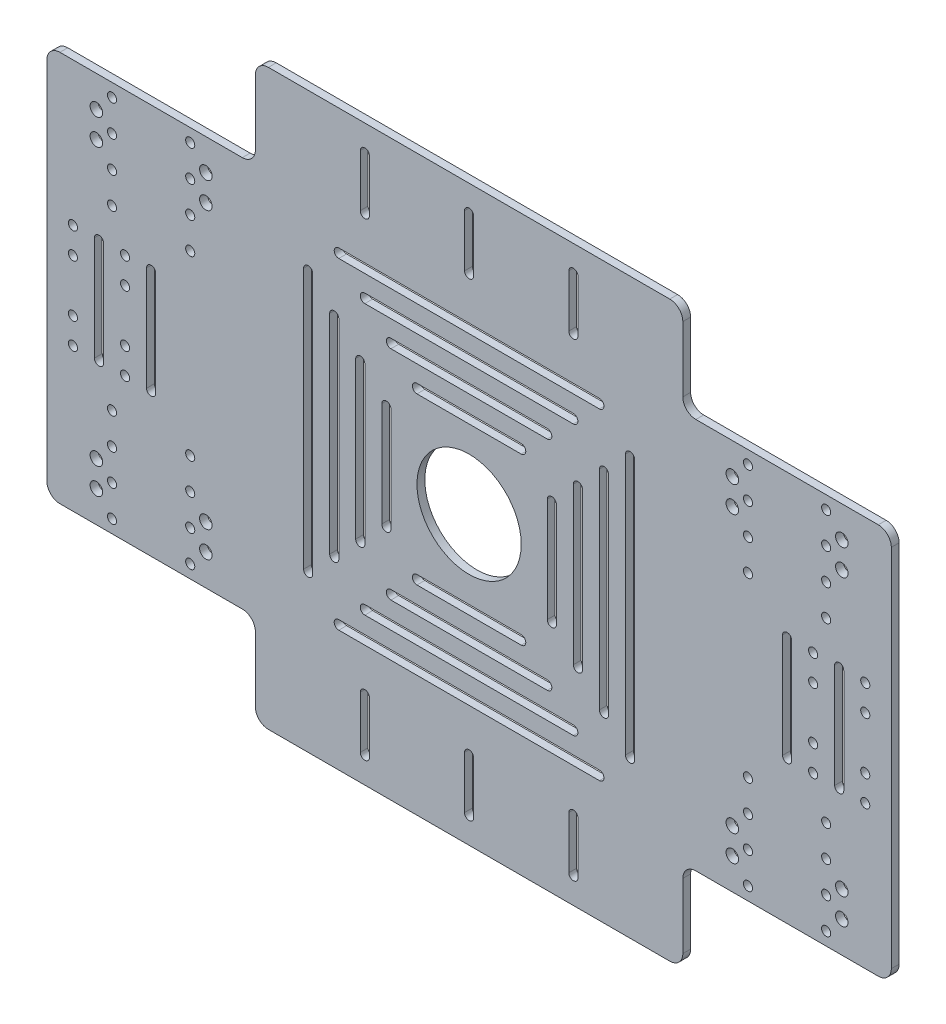
SolidWorks part; units mm, degrees
ref_plane "Front Plane" through (0, 0, 0) normal (0, 0, 1) x (1, 0, 0)
ref_plane "Top Plane" through (0, 0, 0) normal (0, 1, 0) x (1, 0, 0)
ref_plane "Right Plane" through (0, 0, 0) normal (1, 0, 0) x (0, 0, -1)
sketch "Model" plane through (0, 0, 0) normal (0, 0, 1) x (1, 0, 0)
  line L0 (-287, 200) -> (-287, -200)
  line L1 (-287, -200) -> (287, -200)
  line L2 (287, -200) -> (287, 200)
  line L3 (287, 200) -> (-287, 200)
  line L4 (287, -200) -> (287, -144)
  line L5 (287, -144) -> (107, -144)
  line L6 (107, -144) -> (107, -200)
  line L7 (287, -200) -> (107, -200)
  line L8 (187, -144) -> (187, -200)
  line L9 (237, -144) -> (237, -200)
  line L10 (187, -193) -> (107, -193)
  line L11 (187, -186) -> (107, -186)
  line L12 (187, -179) -> (107, -179)
  line L13 (147, -172) -> (147, -200)
  line L14 (213, -172) -> (213, -191)
  line L15 (225, -172) -> (225, -191)
  line L16 (237, -172) -> (107, -172)
  line L17 (287, -179) -> (237, -179)
  line L18 (287, -161) -> (237, -161)
  line L19 (287, -191) -> (187, -191)
  line L20 (-119.2105, 180.4807) -> (-119.2105, 155.4807)
  line L21 (-119.2105, -4.5193) -> (-119.2105, -29.5193)
  line L22 (44.7895, -29.5193) -> (44.7895, -4.5193)
  line L23 (44.7895, 155.4807) -> (44.7895, 180.4807)
  line L24 (39.7895, 185.4807) -> (-99.2105, 185.4807)
  line L25 (-99.2105, 185.4807) -> (-114.2105, 185.4807)
  line L26 (-114.2105, -34.5193) -> (-96.2105, -34.5193)
  line L27 (-96.2105, -34.5193) -> (39.7895, -34.5193)
  line L28 (124.7895, 5.4807) -> (124.7895, 76.9807)
  line L29 (124.7895, 76.9807) -> (124.7895, 145.4807)
  line L30 (-199.2105, 145.4807) -> (-199.2105, 76.9807)
  line L31 (-199.2105, 76.9807) -> (-199.2105, 5.4807)
  line L32 (-124.2105, 150.4807) -> (-194.2105, 150.4807)
  line L33 (-124.2105, 0.4807) -> (-194.2105, 0.4807)
  line L34 (49.7895, 0.4807) -> (119.7895, 0.4807)
  line L35 (49.7895, 150.4807) -> (119.7895, 150.4807)
  line L36 (-17.2105, 105.4807) -> (-37.2105, 105.4807)
  line L37 (-7.2105, 115.4807) -> (-37.2105, 115.4807)
  line L38 (2.7895, 125.4807) -> (-37.2105, 125.4807)
  line L39 (12.7895, 135.4807) -> (-37.2105, 135.4807)
  line L40 (-17.2105, 108.9807) -> (-37.2105, 108.9807)
  line L41 (-7.2105, 118.9807) -> (-37.2105, 118.9807)
  line L42 (2.7895, 128.9807) -> (-37.2105, 128.9807)
  line L43 (12.7895, 138.9807) -> (-37.2105, 138.9807)
  line L44 (-57.2105, 105.4807) -> (-37.2105, 105.4807)
  line L45 (-67.2105, 115.4807) -> (-37.2105, 115.4807)
  line L46 (-77.2105, 125.4807) -> (-37.2105, 125.4807)
  line L47 (-87.2105, 135.4807) -> (-37.2105, 135.4807)
  line L48 (-57.2105, 108.9807) -> (-37.2105, 108.9807)
  line L49 (-67.2105, 118.9807) -> (-37.2105, 118.9807)
  line L50 (-77.2105, 128.9807) -> (-37.2105, 128.9807)
  line L51 (-87.2105, 138.9807) -> (-37.2105, 138.9807)
  line L52 (-67.2105, 95.4807) -> (-67.2105, 75.4807)
  line L53 (-77.2105, 105.4807) -> (-77.2105, 75.4807)
  line L54 (-87.2105, 115.4807) -> (-87.2105, 75.4807)
  line L55 (-97.2105, 125.4807) -> (-97.2105, 75.4807)
  line L56 (-70.7105, 95.4807) -> (-70.7105, 75.4807)
  line L57 (-80.7105, 105.4807) -> (-80.7105, 75.4807)
  line L58 (-90.7105, 115.4807) -> (-90.7105, 75.4807)
  line L59 (-100.7105, 125.4807) -> (-100.7105, 75.4807)
  line L60 (-67.2105, 55.4807) -> (-67.2105, 75.4807)
  line L61 (-77.2105, 45.4807) -> (-77.2105, 75.4807)
  line L62 (-87.2105, 35.4807) -> (-87.2105, 75.4807)
  line L63 (-97.2105, 25.4807) -> (-97.2105, 75.4807)
  line L64 (-70.7105, 55.4807) -> (-70.7105, 75.4807)
  line L65 (-80.7105, 45.4807) -> (-80.7105, 75.4807)
  line L66 (-90.7105, 35.4807) -> (-90.7105, 75.4807)
  line L67 (-100.7105, 25.4807) -> (-100.7105, 75.4807)
  line L68 (-57.2105, 45.4807) -> (-37.2105, 45.4807)
  line L69 (-67.2105, 35.4807) -> (-37.2105, 35.4807)
  line L70 (-77.2105, 25.4807) -> (-37.2105, 25.4807)
  line L71 (-87.2105, 15.4807) -> (-37.2105, 15.4807)
  line L72 (-57.2105, 41.9807) -> (-37.2105, 41.9807)
  line L73 (-67.2105, 31.9807) -> (-37.2105, 31.9807)
  line L74 (-77.2105, 21.9807) -> (-37.2105, 21.9807)
  line L75 (-87.2105, 11.9807) -> (-37.2105, 11.9807)
  line L76 (-17.2105, 45.4807) -> (-37.2105, 45.4807)
  line L77 (-7.2105, 35.4807) -> (-37.2105, 35.4807)
  line L78 (2.7895, 25.4807) -> (-37.2105, 25.4807)
  line L79 (12.7895, 15.4807) -> (-37.2105, 15.4807)
  line L80 (-17.2105, 41.9807) -> (-37.2105, 41.9807)
  line L81 (-7.2105, 31.9807) -> (-37.2105, 31.9807)
  line L82 (2.7895, 21.9807) -> (-37.2105, 21.9807)
  line L83 (12.7895, 11.9807) -> (-37.2105, 11.9807)
  line L84 (-7.2105, 55.4807) -> (-7.2105, 75.4807)
  line L85 (2.7895, 45.4807) -> (2.7895, 75.4807)
  line L86 (12.7895, 35.4807) -> (12.7895, 75.4807)
  line L87 (22.7895, 25.4807) -> (22.7895, 75.4807)
  line L88 (-3.7105, 55.4807) -> (-3.7105, 75.4807)
  line L89 (6.2895, 45.4807) -> (6.2895, 75.4807)
  line L90 (16.2895, 35.4807) -> (16.2895, 75.4807)
  line L91 (26.2895, 25.4807) -> (26.2895, 75.4807)
  line L92 (-7.2105, 95.4807) -> (-7.2105, 75.4807)
  line L93 (2.7895, 105.4807) -> (2.7895, 75.4807)
  line L94 (12.7895, 115.4807) -> (12.7895, 75.4807)
  line L95 (22.7895, 125.4807) -> (22.7895, 75.4807)
  line L96 (-3.7105, 95.4807) -> (-3.7105, 75.4807)
  line L97 (6.2895, 105.4807) -> (6.2895, 75.4807)
  line L98 (16.2895, 115.4807) -> (16.2895, 75.4807)
  line L99 (26.2895, 125.4807) -> (26.2895, 75.4807)
  line L100 (-180.9605, 95.4807) -> (-180.9605, 55.4807)
  line L101 (-177.4605, 95.4807) -> (-177.4605, 55.4807)
  line L102 (-160.9605, 95.4807) -> (-160.9605, 55.4807)
  line L103 (-157.4605, 95.4807) -> (-157.4605, 55.4807)
  line L104 (106.5395, 95.4807) -> (106.5395, 55.4807)
  line L105 (103.0395, 95.4807) -> (103.0395, 55.4807)
  line L106 (86.5395, 95.4807) -> (86.5395, 55.4807)
  line L107 (83.0395, 95.4807) -> (83.0395, 55.4807)
  line L108 (-78.9605, 175.4807) -> (-78.9605, 155.4807)
  line L109 (-75.4605, 175.4807) -> (-75.4605, 155.4807)
  line L110 (-38.9605, 175.4807) -> (-38.9605, 155.4807)
  line L111 (-35.4605, 175.4807) -> (-35.4605, 155.4807)
  line L112 (4.5395, 175.4807) -> (4.5395, 155.4807)
  line L113 (1.0395, 175.4807) -> (1.0395, 155.4807)
  line L114 (-78.9605, -24.5193) -> (-78.9605, -4.5193)
  line L115 (-75.4605, -24.5193) -> (-75.4605, -4.5193)
  line L116 (-38.9605, -24.5193) -> (-38.9605, -4.5193)
  line L117 (-35.4605, -24.5193) -> (-35.4605, -4.5193)
  line L118 (4.5395, -24.5193) -> (4.5395, -4.5193)
  line L119 (1.0395, -24.5193) -> (1.0395, -4.5193)
  line L120 (210.9858, 185.4807) -> (213.9858, 185.4807)
  line L121 (213.9858, 185.4807) -> (213.9858, -33.4042)
  line L122 (210.9858, 185.4807) -> (210.9858, -33.4042)
  line L123 (210.9858, -33.4042) -> (213.9858, -33.4042)
  line L124 (210.9858, 150.4807) -> (213.9858, 150.4807)
  line L125 (210.9858, 0.4807) -> (213.9858, 0.4807)
  circle A0 centre (-180.2105, 138.4807) radius 2.4
  circle A1 centre (-138.2105, 138.4807) radius 2.4
  circle A2 centre (-180.2105, 128.4807) radius 2.4
  circle A3 centre (-138.2105, 128.4807) radius 2.4
  circle A4 centre (-180.2105, 12.4807) radius 2.4
  circle A5 centre (-138.2105, 12.4807) radius 2.4
  circle A6 centre (-180.2105, 22.4807) radius 2.4
  circle A7 centre (-138.2105, 22.4807) radius 2.4
  circle A8 centre (105.7895, 12.4807) radius 2.4
  circle A9 centre (63.7895, 12.4807) radius 2.4
  circle A10 centre (105.7895, 22.4807) radius 2.4
  circle A11 centre (63.7895, 22.4807) radius 2.4
  circle A12 centre (105.7895, 138.4807) radius 2.4
  circle A13 centre (63.7895, 138.4807) radius 2.4
  circle A14 centre (105.7895, 128.4807) radius 2.4
  circle A15 centre (63.7895, 128.4807) radius 2.4
  circle A16 centre (-144.2105, 17.4807) radius 1.75
  circle A17 centre (-144.2105, 5.4807) radius 1.75
  circle A18 centre (-144.2105, 29.4807) radius 1.75
  circle A19 centre (-144.2105, 41.4807) radius 1.75
  circle A20 centre (-174.2105, 17.4807) radius 1.75
  circle A21 centre (-174.2105, 5.4807) radius 1.75
  circle A22 centre (-174.2105, 29.4807) radius 1.75
  circle A23 centre (-174.2105, 41.4807) radius 1.75
  circle A24 centre (-144.2105, 133.4807) radius 1.75
  circle A25 centre (-144.2105, 145.4807) radius 1.75
  circle A26 centre (-144.2105, 121.4807) radius 1.75
  circle A27 centre (-144.2105, 109.4807) radius 1.75
  circle A28 centre (-174.2105, 133.4807) radius 1.75
  circle A29 centre (-174.2105, 145.4807) radius 1.75
  circle A30 centre (-174.2105, 121.4807) radius 1.75
  circle A31 centre (-174.2105, 109.4807) radius 1.75
  circle A32 centre (69.7895, 133.4807) radius 1.75
  circle A33 centre (69.7895, 145.4807) radius 1.75
  circle A34 centre (69.7895, 121.4807) radius 1.75
  circle A35 centre (69.7895, 109.4807) radius 1.75
  circle A36 centre (99.7895, 133.4807) radius 1.75
  circle A37 centre (99.7895, 145.4807) radius 1.75
  circle A38 centre (99.7895, 121.4807) radius 1.75
  circle A39 centre (99.7895, 109.4807) radius 1.75
  circle A40 centre (69.7895, 17.4807) radius 1.75
  circle A41 centre (69.7895, 5.4807) radius 1.75
  circle A42 centre (69.7895, 29.4807) radius 1.75
  circle A43 centre (69.7895, 41.4807) radius 1.75
  circle A44 centre (99.7895, 17.4807) radius 1.75
  circle A45 centre (99.7895, 5.4807) radius 1.75
  circle A46 centre (99.7895, 29.4807) radius 1.75
  circle A47 centre (99.7895, 41.4807) radius 1.75
  arc A48 (-194.2105, 150.4807) -> (-199.2105, 145.4807) centre (-194.2105, 145.4807) ccw
  arc A49 (-124.2105, 150.4807) -> (-119.2105, 155.4807) centre (-124.2105, 155.4807) ccw
  arc A50 (-199.2105, 5.4807) -> (-194.2105, 0.4807) centre (-194.2105, 5.4807) ccw
  arc A51 (-119.2105, -4.5193) -> (-124.2105, 0.4807) centre (-124.2105, -4.5193) ccw
  arc A52 (-119.2105, -29.5193) -> (-114.2105, -34.5193) centre (-114.2105, -29.5193) ccw
  arc A53 (39.7895, -34.5193) -> (44.7895, -29.5193) centre (39.7895, -29.5193) ccw
  arc A54 (49.7895, 0.4807) -> (44.7895, -4.5193) centre (49.7895, -4.5193) ccw
  arc A55 (119.7895, 0.4807) -> (124.7895, 5.4807) centre (119.7895, 5.4807) ccw
  arc A56 (124.7895, 145.4807) -> (119.7895, 150.4807) centre (119.7895, 145.4807) ccw
  arc A57 (44.7895, 155.4807) -> (49.7895, 150.4807) centre (49.7895, 155.4807) ccw
  arc A58 (44.7895, 180.4807) -> (39.7895, 185.4807) centre (39.7895, 180.4807) ccw
  arc A59 (-114.2105, 185.4807) -> (-119.2105, 180.4807) centre (-114.2105, 180.4807) ccw
  circle A60 centre (-37.2105, 75.4807) radius 20
  arc A61 (12.7895, 135.4807) -> (12.7895, 138.9807) centre (12.7895, 137.2307) ccw
  arc A62 (2.7895, 125.4807) -> (2.7895, 128.9807) centre (2.7895, 127.2307) ccw
  arc A63 (-7.2105, 115.4807) -> (-7.2105, 118.9807) centre (-7.2105, 117.2307) ccw
  arc A64 (-17.2105, 105.4807) -> (-17.2105, 108.9807) centre (-17.2105, 107.2307) ccw
  arc A65 (-87.2105, 138.9807) -> (-87.2105, 135.4807) centre (-87.2105, 137.2307) ccw
  arc A66 (-77.2105, 128.9807) -> (-77.2105, 125.4807) centre (-77.2105, 127.2307) ccw
  arc A67 (-67.2105, 118.9807) -> (-67.2105, 115.4807) centre (-67.2105, 117.2307) ccw
  arc A68 (-57.2105, 108.9807) -> (-57.2105, 105.4807) centre (-57.2105, 107.2307) ccw
  arc A69 (-97.2105, 125.4807) -> (-100.7105, 125.4807) centre (-98.9605, 125.4807) ccw
  arc A70 (-87.2105, 115.4807) -> (-90.7105, 115.4807) centre (-88.9605, 115.4807) ccw
  arc A71 (-77.2105, 105.4807) -> (-80.7105, 105.4807) centre (-78.9605, 105.4807) ccw
  arc A72 (-67.2105, 95.4807) -> (-70.7105, 95.4807) centre (-68.9605, 95.4807) ccw
  arc A73 (-100.7105, 25.4807) -> (-97.2105, 25.4807) centre (-98.9605, 25.4807) ccw
  arc A74 (-90.7105, 35.4807) -> (-87.2105, 35.4807) centre (-88.9605, 35.4807) ccw
  arc A75 (-80.7105, 45.4807) -> (-77.2105, 45.4807) centre (-78.9605, 45.4807) ccw
  arc A76 (-70.7105, 55.4807) -> (-67.2105, 55.4807) centre (-68.9605, 55.4807) ccw
  arc A77 (-87.2105, 15.4807) -> (-87.2105, 11.9807) centre (-87.2105, 13.7307) ccw
  arc A78 (-77.2105, 25.4807) -> (-77.2105, 21.9807) centre (-77.2105, 23.7307) ccw
  arc A79 (-67.2105, 35.4807) -> (-67.2105, 31.9807) centre (-67.2105, 33.7307) ccw
  arc A80 (-57.2105, 45.4807) -> (-57.2105, 41.9807) centre (-57.2105, 43.7307) ccw
  arc A81 (12.7895, 11.9807) -> (12.7895, 15.4807) centre (12.7895, 13.7307) ccw
  arc A82 (2.7895, 21.9807) -> (2.7895, 25.4807) centre (2.7895, 23.7307) ccw
  arc A83 (-7.2105, 31.9807) -> (-7.2105, 35.4807) centre (-7.2105, 33.7307) ccw
  arc A84 (-17.2105, 41.9807) -> (-17.2105, 45.4807) centre (-17.2105, 43.7307) ccw
  arc A85 (22.7895, 25.4807) -> (26.2895, 25.4807) centre (24.5395, 25.4807) ccw
  arc A86 (12.7895, 35.4807) -> (16.2895, 35.4807) centre (14.5395, 35.4807) ccw
  arc A87 (2.7895, 45.4807) -> (6.2895, 45.4807) centre (4.5395, 45.4807) ccw
  arc A88 (-7.2105, 55.4807) -> (-3.7105, 55.4807) centre (-5.4605, 55.4807) ccw
  arc A89 (26.2895, 125.4807) -> (22.7895, 125.4807) centre (24.5395, 125.4807) ccw
  arc A90 (16.2895, 115.4807) -> (12.7895, 115.4807) centre (14.5395, 115.4807) ccw
  arc A91 (6.2895, 105.4807) -> (2.7895, 105.4807) centre (4.5395, 105.4807) ccw
  arc A92 (-3.7105, 95.4807) -> (-7.2105, 95.4807) centre (-5.4605, 95.4807) ccw
  circle A93 centre (-189.2105, 85.4807) radius 1.75
  circle A94 centre (-189.2105, 95.4807) radius 1.75
  circle A95 centre (-169.2105, 95.4807) radius 1.75
  circle A96 centre (-169.2105, 85.4807) radius 1.75
  circle A97 centre (-189.2105, 65.4807) radius 1.75
  circle A98 centre (-189.2105, 55.4807) radius 1.75
  circle A99 centre (-169.2105, 55.4807) radius 1.75
  circle A100 centre (-169.2105, 65.4807) radius 1.75
  arc A101 (-177.4605, 95.4807) -> (-180.9605, 95.4807) centre (-179.2105, 95.4807) ccw
  arc A102 (-180.9605, 55.4807) -> (-177.4605, 55.4807) centre (-179.2105, 55.4807) ccw
  arc A103 (-160.9605, 55.4807) -> (-157.4605, 55.4807) centre (-159.2105, 55.4807) ccw
  arc A104 (-157.4605, 95.4807) -> (-160.9605, 95.4807) centre (-159.2105, 95.4807) ccw
  circle A105 centre (114.7895, 85.4807) radius 1.75
  circle A106 centre (114.7895, 95.4807) radius 1.75
  circle A107 centre (94.7895, 95.4807) radius 1.75
  circle A108 centre (94.7895, 85.4807) radius 1.75
  circle A109 centre (114.7895, 65.4807) radius 1.75
  circle A110 centre (114.7895, 55.4807) radius 1.75
  circle A111 centre (94.7895, 55.4807) radius 1.75
  circle A112 centre (94.7895, 65.4807) radius 1.75
  arc A113 (106.5395, 95.4807) -> (103.0395, 95.4807) centre (104.7895, 95.4807) ccw
  arc A114 (103.0395, 55.4807) -> (106.5395, 55.4807) centre (104.7895, 55.4807) ccw
  arc A115 (83.0395, 55.4807) -> (86.5395, 55.4807) centre (84.7895, 55.4807) ccw
  arc A116 (86.5395, 95.4807) -> (83.0395, 95.4807) centre (84.7895, 95.4807) ccw
  arc A117 (-75.4605, 175.4807) -> (-78.9605, 175.4807) centre (-77.2105, 175.4807) ccw
  arc A118 (-78.9605, 155.4807) -> (-75.4605, 155.4807) centre (-77.2105, 155.4807) ccw
  arc A119 (-38.9605, 155.4807) -> (-35.4605, 155.4807) centre (-37.2105, 155.4807) ccw
  arc A120 (-35.4605, 175.4807) -> (-38.9605, 175.4807) centre (-37.2105, 175.4807) ccw
  arc A121 (4.5395, 175.4807) -> (1.0395, 175.4807) centre (2.7895, 175.4807) ccw
  arc A122 (1.0395, 155.4807) -> (4.5395, 155.4807) centre (2.7895, 155.4807) ccw
  arc A123 (-78.9605, -24.5193) -> (-75.4605, -24.5193) centre (-77.2105, -24.5193) ccw
  arc A124 (-75.4605, -4.5193) -> (-78.9605, -4.5193) centre (-77.2105, -4.5193) ccw
  arc A125 (-35.4605, -4.5193) -> (-38.9605, -4.5193) centre (-37.2105, -4.5193) ccw
  arc A126 (-38.9605, -24.5193) -> (-35.4605, -24.5193) centre (-37.2105, -24.5193) ccw
  arc A127 (1.0395, -24.5193) -> (4.5395, -24.5193) centre (2.7895, -24.5193) ccw
  arc A128 (4.5395, -4.5193) -> (1.0395, -4.5193) centre (2.7895, -4.5193) ccw
sketch "Sketch2" plane through (0, 0, 0) normal (0, 0, 1) x (1, 0, 0)
  line L0 (-124.2105, 150.4807) -> (-194.2105, 150.4807) construction
  line L1 (-119.2105, 180.4807) -> (-119.2105, 155.4807) construction
  line L2 (-99.2105, 185.4807) -> (-114.2105, 185.4807) construction
  line L3 (39.7895, 185.4807) -> (-99.2105, 185.4807) construction
  line L4 (44.7895, 155.4807) -> (44.7895, 180.4807) construction
  line L5 (49.7895, 150.4807) -> (119.7895, 150.4807) construction
  line L6 (124.7895, 76.9807) -> (124.7895, 145.4807) construction
  line L7 (124.7895, 5.4807) -> (124.7895, 76.9807) construction
  line L8 (49.7895, 0.4807) -> (119.7895, 0.4807) construction
  line L9 (44.7895, -29.5193) -> (44.7895, -4.5193) construction
  line L10 (-96.2105, -34.5193) -> (39.7895, -34.5193) construction
  line L11 (-114.2105, -34.5193) -> (-96.2105, -34.5193) construction
  line L12 (-119.2105, -4.5193) -> (-119.2105, -29.5193) construction
  line L13 (-124.2105, 0.4807) -> (-194.2105, 0.4807) construction
  line L14 (-199.2105, 76.9807) -> (-199.2105, 5.4807) construction
  line L15 (-199.2105, 145.4807) -> (-199.2105, 76.9807) construction
  line L16 (-124.2105, 150.4807) -> (-194.2105, 150.4807)
  line L17 (-119.2105, 180.4807) -> (-119.2105, 155.4807)
  line L18 (-99.2105, 185.4807) -> (-114.2105, 185.4807)
  line L19 (39.7895, 185.4807) -> (-99.2105, 185.4807)
  line L20 (44.7895, 155.4807) -> (44.7895, 180.4807)
  line L21 (49.7895, 150.4807) -> (119.7895, 150.4807)
  line L22 (124.7895, 76.9807) -> (124.7895, 145.4807)
  line L23 (124.7895, 5.4807) -> (124.7895, 76.9807)
  line L24 (49.7895, 0.4807) -> (119.7895, 0.4807)
  line L25 (44.7895, -29.5193) -> (44.7895, -4.5193)
  line L26 (-96.2105, -34.5193) -> (39.7895, -34.5193)
  line L27 (-114.2105, -34.5193) -> (-96.2105, -34.5193)
  line L28 (-119.2105, -4.5193) -> (-119.2105, -29.5193)
  line L29 (-124.2105, 0.4807) -> (-194.2105, 0.4807)
  line L30 (-199.2105, 76.9807) -> (-199.2105, 5.4807)
  line L31 (-199.2105, 145.4807) -> (-199.2105, 76.9807)
  line L32 (-78.9605, 175.4807) -> (-78.9605, 155.4807) construction
  line L33 (-75.4605, 175.4807) -> (-75.4605, 155.4807) construction
  line L34 (-78.9605, 175.4807) -> (-78.9605, 155.4807)
  line L35 (-75.4605, 175.4807) -> (-75.4605, 155.4807)
  line L36 (-38.9605, 175.4807) -> (-38.9605, 155.4807) construction
  line L37 (-35.4605, 175.4807) -> (-35.4605, 155.4807) construction
  line L38 (-38.9605, 175.4807) -> (-38.9605, 155.4807)
  line L39 (-35.4605, 175.4807) -> (-35.4605, 155.4807)
  line L40 (4.5395, 175.4807) -> (4.5395, 155.4807) construction
  line L41 (1.0395, 175.4807) -> (1.0395, 155.4807) construction
  line L42 (4.5395, 175.4807) -> (4.5395, 155.4807)
  line L43 (1.0395, 175.4807) -> (1.0395, 155.4807)
  line L44 (-87.2105, 138.9807) -> (-37.2105, 138.9807) construction
  line L45 (12.7895, 138.9807) -> (-37.2105, 138.9807) construction
  line L46 (12.7895, 135.4807) -> (-37.2105, 135.4807) construction
  line L47 (-87.2105, 135.4807) -> (-37.2105, 135.4807) construction
  line L48 (-87.2105, 138.9807) -> (-37.2105, 138.9807)
  line L49 (12.7895, 138.9807) -> (-37.2105, 138.9807)
  line L50 (12.7895, 135.4807) -> (-37.2105, 135.4807)
  line L51 (-87.2105, 135.4807) -> (-37.2105, 135.4807)
  line L52 (-77.2105, 128.9807) -> (-37.2105, 128.9807) construction
  line L53 (2.7895, 128.9807) -> (-37.2105, 128.9807) construction
  line L54 (2.7895, 125.4807) -> (-37.2105, 125.4807) construction
  line L55 (-77.2105, 125.4807) -> (-37.2105, 125.4807) construction
  line L56 (-77.2105, 128.9807) -> (-37.2105, 128.9807)
  line L57 (2.7895, 128.9807) -> (-37.2105, 128.9807)
  line L58 (2.7895, 125.4807) -> (-37.2105, 125.4807)
  line L59 (-77.2105, 125.4807) -> (-37.2105, 125.4807)
  line L60 (-67.2105, 118.9807) -> (-37.2105, 118.9807) construction
  line L61 (-7.2105, 118.9807) -> (-37.2105, 118.9807) construction
  line L62 (-7.2105, 115.4807) -> (-37.2105, 115.4807) construction
  line L63 (-67.2105, 115.4807) -> (-37.2105, 115.4807) construction
  line L64 (-67.2105, 118.9807) -> (-37.2105, 118.9807)
  line L65 (-7.2105, 118.9807) -> (-37.2105, 118.9807)
  line L66 (-7.2105, 115.4807) -> (-37.2105, 115.4807)
  line L67 (-67.2105, 115.4807) -> (-37.2105, 115.4807)
  line L68 (-57.2105, 108.9807) -> (-37.2105, 108.9807) construction
  line L69 (-17.2105, 108.9807) -> (-37.2105, 108.9807) construction
  line L70 (-17.2105, 105.4807) -> (-37.2105, 105.4807) construction
  line L71 (-57.2105, 105.4807) -> (-37.2105, 105.4807) construction
  line L72 (-57.2105, 108.9807) -> (-37.2105, 108.9807)
  line L73 (-17.2105, 108.9807) -> (-37.2105, 108.9807)
  line L74 (-17.2105, 105.4807) -> (-37.2105, 105.4807)
  line L75 (-57.2105, 105.4807) -> (-37.2105, 105.4807)
  line L76 (-100.7105, 25.4807) -> (-100.7105, 75.4807) construction
  line L77 (-100.7105, 125.4807) -> (-100.7105, 75.4807) construction
  line L78 (-97.2105, 125.4807) -> (-97.2105, 75.4807) construction
  line L79 (-97.2105, 25.4807) -> (-97.2105, 75.4807) construction
  line L80 (-100.7105, 25.4807) -> (-100.7105, 75.4807)
  line L81 (-100.7105, 125.4807) -> (-100.7105, 75.4807)
  line L82 (-97.2105, 125.4807) -> (-97.2105, 75.4807)
  line L83 (-97.2105, 25.4807) -> (-97.2105, 75.4807)
  line L84 (-90.7105, 115.4807) -> (-90.7105, 75.4807) construction
  line L85 (-90.7105, 35.4807) -> (-90.7105, 75.4807) construction
  line L86 (-87.2105, 35.4807) -> (-87.2105, 75.4807) construction
  line L87 (-87.2105, 115.4807) -> (-87.2105, 75.4807) construction
  line L88 (-90.7105, 115.4807) -> (-90.7105, 75.4807)
  line L89 (-90.7105, 35.4807) -> (-90.7105, 75.4807)
  line L90 (-87.2105, 35.4807) -> (-87.2105, 75.4807)
  line L91 (-87.2105, 115.4807) -> (-87.2105, 75.4807)
  line L92 (-80.7105, 105.4807) -> (-80.7105, 75.4807) construction
  line L93 (-80.7105, 45.4807) -> (-80.7105, 75.4807) construction
  line L94 (-77.2105, 45.4807) -> (-77.2105, 75.4807) construction
  line L95 (-77.2105, 105.4807) -> (-77.2105, 75.4807) construction
  line L96 (-80.7105, 105.4807) -> (-80.7105, 75.4807)
  line L97 (-80.7105, 45.4807) -> (-80.7105, 75.4807)
  line L98 (-77.2105, 45.4807) -> (-77.2105, 75.4807)
  line L99 (-77.2105, 105.4807) -> (-77.2105, 75.4807)
  line L100 (-70.7105, 95.4807) -> (-70.7105, 75.4807) construction
  line L101 (-70.7105, 55.4807) -> (-70.7105, 75.4807) construction
  line L102 (-67.2105, 55.4807) -> (-67.2105, 75.4807) construction
  line L103 (-67.2105, 95.4807) -> (-67.2105, 75.4807) construction
  line L104 (-70.7105, 95.4807) -> (-70.7105, 75.4807)
  line L105 (-70.7105, 55.4807) -> (-70.7105, 75.4807)
  line L106 (-67.2105, 55.4807) -> (-67.2105, 75.4807)
  line L107 (-67.2105, 95.4807) -> (-67.2105, 75.4807)
  line L108 (-160.9605, 95.4807) -> (-160.9605, 55.4807) construction
  line L109 (-157.4605, 95.4807) -> (-157.4605, 55.4807) construction
  line L110 (-160.9605, 95.4807) -> (-160.9605, 55.4807)
  line L111 (-157.4605, 95.4807) -> (-157.4605, 55.4807)
  line L112 (-180.9605, 95.4807) -> (-180.9605, 55.4807) construction
  line L113 (-177.4605, 95.4807) -> (-177.4605, 55.4807) construction
  line L114 (-180.9605, 95.4807) -> (-180.9605, 55.4807)
  line L115 (-177.4605, 95.4807) -> (-177.4605, 55.4807)
  line L116 (-57.2105, 45.4807) -> (-37.2105, 45.4807) construction
  line L117 (-17.2105, 45.4807) -> (-37.2105, 45.4807) construction
  line L118 (-17.2105, 41.9807) -> (-37.2105, 41.9807) construction
  line L119 (-57.2105, 41.9807) -> (-37.2105, 41.9807) construction
  line L120 (-67.2105, 35.4807) -> (-37.2105, 35.4807) construction
  line L121 (-7.2105, 35.4807) -> (-37.2105, 35.4807) construction
  line L122 (-7.2105, 31.9807) -> (-37.2105, 31.9807) construction
  line L123 (-67.2105, 31.9807) -> (-37.2105, 31.9807) construction
  line L124 (-77.2105, 25.4807) -> (-37.2105, 25.4807) construction
  line L125 (2.7895, 25.4807) -> (-37.2105, 25.4807) construction
  line L126 (2.7895, 21.9807) -> (-37.2105, 21.9807) construction
  line L127 (-77.2105, 21.9807) -> (-37.2105, 21.9807) construction
  line L128 (-87.2105, 15.4807) -> (-37.2105, 15.4807) construction
  line L129 (12.7895, 15.4807) -> (-37.2105, 15.4807) construction
  line L130 (12.7895, 11.9807) -> (-37.2105, 11.9807) construction
  line L131 (-87.2105, 11.9807) -> (-37.2105, 11.9807) construction
  line L132 (-57.2105, 45.4807) -> (-37.2105, 45.4807)
  line L133 (-17.2105, 45.4807) -> (-37.2105, 45.4807)
  line L134 (-17.2105, 41.9807) -> (-37.2105, 41.9807)
  line L135 (-57.2105, 41.9807) -> (-37.2105, 41.9807)
  line L136 (-67.2105, 35.4807) -> (-37.2105, 35.4807)
  line L137 (-7.2105, 35.4807) -> (-37.2105, 35.4807)
  line L138 (-7.2105, 31.9807) -> (-37.2105, 31.9807)
  line L139 (-67.2105, 31.9807) -> (-37.2105, 31.9807)
  line L140 (-77.2105, 25.4807) -> (-37.2105, 25.4807)
  line L141 (2.7895, 25.4807) -> (-37.2105, 25.4807)
  line L142 (2.7895, 21.9807) -> (-37.2105, 21.9807)
  line L143 (-77.2105, 21.9807) -> (-37.2105, 21.9807)
  line L144 (-87.2105, 15.4807) -> (-37.2105, 15.4807)
  line L145 (12.7895, 15.4807) -> (-37.2105, 15.4807)
  line L146 (12.7895, 11.9807) -> (-37.2105, 11.9807)
  line L147 (-87.2105, 11.9807) -> (-37.2105, 11.9807)
  line L148 (22.7895, 25.4807) -> (22.7895, 75.4807) construction
  line L149 (22.7895, 125.4807) -> (22.7895, 75.4807) construction
  line L150 (26.2895, 125.4807) -> (26.2895, 75.4807) construction
  line L151 (26.2895, 25.4807) -> (26.2895, 75.4807) construction
  line L152 (12.7895, 35.4807) -> (12.7895, 75.4807) construction
  line L153 (12.7895, 115.4807) -> (12.7895, 75.4807) construction
  line L154 (16.2895, 115.4807) -> (16.2895, 75.4807) construction
  line L155 (16.2895, 35.4807) -> (16.2895, 75.4807) construction
  line L156 (2.7895, 45.4807) -> (2.7895, 75.4807) construction
  line L157 (2.7895, 105.4807) -> (2.7895, 75.4807) construction
  line L158 (6.2895, 105.4807) -> (6.2895, 75.4807) construction
  line L159 (6.2895, 45.4807) -> (6.2895, 75.4807) construction
  line L160 (-7.2105, 55.4807) -> (-7.2105, 75.4807) construction
  line L161 (-7.2105, 95.4807) -> (-7.2105, 75.4807) construction
  line L162 (-3.7105, 95.4807) -> (-3.7105, 75.4807) construction
  line L163 (-3.7105, 55.4807) -> (-3.7105, 75.4807) construction
  line L164 (1.0395, -24.5193) -> (1.0395, -4.5193) construction
  line L165 (4.5395, -24.5193) -> (4.5395, -4.5193) construction
  line L166 (-38.9605, -24.5193) -> (-38.9605, -4.5193) construction
  line L167 (-35.4605, -24.5193) -> (-35.4605, -4.5193) construction
  line L168 (-78.9605, -24.5193) -> (-78.9605, -4.5193) construction
  line L169 (-75.4605, -24.5193) -> (-75.4605, -4.5193) construction
  line L170 (22.7895, 25.4807) -> (22.7895, 75.4807)
  line L171 (22.7895, 125.4807) -> (22.7895, 75.4807)
  line L172 (26.2895, 125.4807) -> (26.2895, 75.4807)
  line L173 (26.2895, 25.4807) -> (26.2895, 75.4807)
  line L174 (12.7895, 35.4807) -> (12.7895, 75.4807)
  line L175 (12.7895, 115.4807) -> (12.7895, 75.4807)
  line L176 (16.2895, 115.4807) -> (16.2895, 75.4807)
  line L177 (16.2895, 35.4807) -> (16.2895, 75.4807)
  line L178 (2.7895, 45.4807) -> (2.7895, 75.4807)
  line L179 (2.7895, 105.4807) -> (2.7895, 75.4807)
  line L180 (6.2895, 105.4807) -> (6.2895, 75.4807)
  line L181 (6.2895, 45.4807) -> (6.2895, 75.4807)
  line L182 (-7.2105, 55.4807) -> (-7.2105, 75.4807)
  line L183 (-7.2105, 95.4807) -> (-7.2105, 75.4807)
  line L184 (-3.7105, 95.4807) -> (-3.7105, 75.4807)
  line L185 (-3.7105, 55.4807) -> (-3.7105, 75.4807)
  line L186 (1.0395, -24.5193) -> (1.0395, -4.5193)
  line L187 (4.5395, -24.5193) -> (4.5395, -4.5193)
  line L188 (-38.9605, -24.5193) -> (-38.9605, -4.5193)
  line L189 (-35.4605, -24.5193) -> (-35.4605, -4.5193)
  line L190 (-78.9605, -24.5193) -> (-78.9605, -4.5193)
  line L191 (-75.4605, -24.5193) -> (-75.4605, -4.5193)
  line L192 (106.5395, 95.4807) -> (106.5395, 55.4807) construction
  line L193 (103.0395, 95.4807) -> (103.0395, 55.4807) construction
  line L194 (83.0395, 95.4807) -> (83.0395, 55.4807) construction
  line L195 (86.5395, 95.4807) -> (86.5395, 55.4807) construction
  line L196 (106.5395, 95.4807) -> (106.5395, 55.4807)
  line L197 (103.0395, 95.4807) -> (103.0395, 55.4807)
  line L198 (83.0395, 95.4807) -> (83.0395, 55.4807)
  line L199 (86.5395, 95.4807) -> (86.5395, 55.4807)
  arc A0 (-194.2105, 150.4807) -> (-199.2105, 145.4807) centre (-194.2105, 145.4807) ccw construction
  arc A1 (-124.2105, 150.4807) -> (-119.2105, 155.4807) centre (-124.2105, 155.4807) ccw construction
  arc A2 (-114.2105, 185.4807) -> (-119.2105, 180.4807) centre (-114.2105, 180.4807) ccw construction
  arc A3 (44.7895, 180.4807) -> (39.7895, 185.4807) centre (39.7895, 180.4807) ccw construction
  arc A4 (44.7895, 155.4807) -> (49.7895, 150.4807) centre (49.7895, 155.4807) ccw construction
  arc A5 (124.7895, 145.4807) -> (119.7895, 150.4807) centre (119.7895, 145.4807) ccw construction
  arc A6 (119.7895, 0.4807) -> (124.7895, 5.4807) centre (119.7895, 5.4807) ccw construction
  arc A7 (49.7895, 0.4807) -> (44.7895, -4.5193) centre (49.7895, -4.5193) ccw construction
  arc A8 (39.7895, -34.5193) -> (44.7895, -29.5193) centre (39.7895, -29.5193) ccw construction
  arc A9 (-119.2105, -29.5193) -> (-114.2105, -34.5193) centre (-114.2105, -29.5193) ccw construction
  arc A10 (-119.2105, -4.5193) -> (-124.2105, 0.4807) centre (-124.2105, -4.5193) ccw construction
  arc A11 (-199.2105, 5.4807) -> (-194.2105, 0.4807) centre (-194.2105, 5.4807) ccw construction
  arc A12 (-194.2105, 150.4807) -> (-199.2105, 145.4807) centre (-194.2105, 145.4807) ccw
  arc A13 (-124.2105, 150.4807) -> (-119.2105, 155.4807) centre (-124.2105, 155.4807) ccw
  arc A14 (-114.2105, 185.4807) -> (-119.2105, 180.4807) centre (-114.2105, 180.4807) ccw
  arc A15 (44.7895, 180.4807) -> (39.7895, 185.4807) centre (39.7895, 180.4807) ccw
  arc A16 (44.7895, 155.4807) -> (49.7895, 150.4807) centre (49.7895, 155.4807) ccw
  arc A17 (124.7895, 145.4807) -> (119.7895, 150.4807) centre (119.7895, 145.4807) ccw
  arc A18 (119.7895, 0.4807) -> (124.7895, 5.4807) centre (119.7895, 5.4807) ccw
  arc A19 (49.7895, 0.4807) -> (44.7895, -4.5193) centre (49.7895, -4.5193) ccw
  arc A20 (39.7895, -34.5193) -> (44.7895, -29.5193) centre (39.7895, -29.5193) ccw
  arc A21 (-119.2105, -29.5193) -> (-114.2105, -34.5193) centre (-114.2105, -29.5193) ccw
  arc A22 (-119.2105, -4.5193) -> (-124.2105, 0.4807) centre (-124.2105, -4.5193) ccw
  arc A23 (-199.2105, 5.4807) -> (-194.2105, 0.4807) centre (-194.2105, 5.4807) ccw
  arc A24 (-75.4605, 175.4807) -> (-78.9605, 175.4807) centre (-77.2105, 175.4807) ccw construction
  arc A25 (-78.9605, 155.4807) -> (-75.4605, 155.4807) centre (-77.2105, 155.4807) ccw construction
  arc A26 (-75.4605, 175.4807) -> (-78.9605, 175.4807) centre (-77.2105, 175.4807) ccw
  arc A27 (-78.9605, 155.4807) -> (-75.4605, 155.4807) centre (-77.2105, 155.4807) ccw
  arc A28 (-35.4605, 175.4807) -> (-38.9605, 175.4807) centre (-37.2105, 175.4807) ccw construction
  arc A29 (-38.9605, 155.4807) -> (-35.4605, 155.4807) centre (-37.2105, 155.4807) ccw construction
  arc A30 (-35.4605, 175.4807) -> (-38.9605, 175.4807) centre (-37.2105, 175.4807) ccw
  arc A31 (-38.9605, 155.4807) -> (-35.4605, 155.4807) centre (-37.2105, 155.4807) ccw
  arc A32 (4.5395, 175.4807) -> (1.0395, 175.4807) centre (2.7895, 175.4807) ccw construction
  arc A33 (1.0395, 155.4807) -> (4.5395, 155.4807) centre (2.7895, 155.4807) ccw construction
  arc A34 (4.5395, 175.4807) -> (1.0395, 175.4807) centre (2.7895, 175.4807) ccw
  arc A35 (1.0395, 155.4807) -> (4.5395, 155.4807) centre (2.7895, 155.4807) ccw
  arc A36 (-87.2105, 138.9807) -> (-87.2105, 135.4807) centre (-87.2105, 137.2307) ccw construction
  arc A37 (12.7895, 135.4807) -> (12.7895, 138.9807) centre (12.7895, 137.2307) ccw construction
  arc A38 (-87.2105, 138.9807) -> (-87.2105, 135.4807) centre (-87.2105, 137.2307) ccw
  arc A39 (12.7895, 135.4807) -> (12.7895, 138.9807) centre (12.7895, 137.2307) ccw
  arc A40 (-77.2105, 128.9807) -> (-77.2105, 125.4807) centre (-77.2105, 127.2307) ccw construction
  arc A41 (2.7895, 125.4807) -> (2.7895, 128.9807) centre (2.7895, 127.2307) ccw construction
  arc A42 (-77.2105, 128.9807) -> (-77.2105, 125.4807) centre (-77.2105, 127.2307) ccw
  arc A43 (2.7895, 125.4807) -> (2.7895, 128.9807) centre (2.7895, 127.2307) ccw
  arc A44 (-67.2105, 118.9807) -> (-67.2105, 115.4807) centre (-67.2105, 117.2307) ccw construction
  arc A45 (-7.2105, 115.4807) -> (-7.2105, 118.9807) centre (-7.2105, 117.2307) ccw construction
  arc A46 (-67.2105, 118.9807) -> (-67.2105, 115.4807) centre (-67.2105, 117.2307) ccw
  arc A47 (-7.2105, 115.4807) -> (-7.2105, 118.9807) centre (-7.2105, 117.2307) ccw
  arc A48 (-57.2105, 108.9807) -> (-57.2105, 105.4807) centre (-57.2105, 107.2307) ccw construction
  arc A49 (-17.2105, 105.4807) -> (-17.2105, 108.9807) centre (-17.2105, 107.2307) ccw construction
  arc A50 (-57.2105, 108.9807) -> (-57.2105, 105.4807) centre (-57.2105, 107.2307) ccw
  arc A51 (-17.2105, 105.4807) -> (-17.2105, 108.9807) centre (-17.2105, 107.2307) ccw
  circle A52 centre (-37.2105, 75.4807) radius 20 construction
  circle A53 centre (-37.2105, 75.4807) radius 20
  arc A54 (-100.7105, 25.4807) -> (-97.2105, 25.4807) centre (-98.9605, 25.4807) ccw construction
  arc A55 (-97.2105, 125.4807) -> (-100.7105, 125.4807) centre (-98.9605, 125.4807) ccw construction
  arc A56 (-100.7105, 25.4807) -> (-97.2105, 25.4807) centre (-98.9605, 25.4807) ccw
  arc A57 (-97.2105, 125.4807) -> (-100.7105, 125.4807) centre (-98.9605, 125.4807) ccw
  arc A58 (-87.2105, 115.4807) -> (-90.7105, 115.4807) centre (-88.9605, 115.4807) ccw construction
  arc A59 (-90.7105, 35.4807) -> (-87.2105, 35.4807) centre (-88.9605, 35.4807) ccw construction
  arc A60 (-87.2105, 115.4807) -> (-90.7105, 115.4807) centre (-88.9605, 115.4807) ccw
  arc A61 (-90.7105, 35.4807) -> (-87.2105, 35.4807) centre (-88.9605, 35.4807) ccw
  arc A62 (-77.2105, 105.4807) -> (-80.7105, 105.4807) centre (-78.9605, 105.4807) ccw construction
  arc A63 (-80.7105, 45.4807) -> (-77.2105, 45.4807) centre (-78.9605, 45.4807) ccw construction
  arc A64 (-77.2105, 105.4807) -> (-80.7105, 105.4807) centre (-78.9605, 105.4807) ccw
  arc A65 (-80.7105, 45.4807) -> (-77.2105, 45.4807) centre (-78.9605, 45.4807) ccw
  arc A66 (-67.2105, 95.4807) -> (-70.7105, 95.4807) centre (-68.9605, 95.4807) ccw construction
  arc A67 (-70.7105, 55.4807) -> (-67.2105, 55.4807) centre (-68.9605, 55.4807) ccw construction
  arc A68 (-67.2105, 95.4807) -> (-70.7105, 95.4807) centre (-68.9605, 95.4807) ccw
  arc A69 (-70.7105, 55.4807) -> (-67.2105, 55.4807) centre (-68.9605, 55.4807) ccw
  arc A70 (-157.4605, 95.4807) -> (-160.9605, 95.4807) centre (-159.2105, 95.4807) ccw construction
  arc A71 (-160.9605, 55.4807) -> (-157.4605, 55.4807) centre (-159.2105, 55.4807) ccw construction
  arc A72 (-157.4605, 95.4807) -> (-160.9605, 95.4807) centre (-159.2105, 95.4807) ccw
  arc A73 (-160.9605, 55.4807) -> (-157.4605, 55.4807) centre (-159.2105, 55.4807) ccw
  arc A74 (-177.4605, 95.4807) -> (-180.9605, 95.4807) centre (-179.2105, 95.4807) ccw construction
  arc A75 (-180.9605, 55.4807) -> (-177.4605, 55.4807) centre (-179.2105, 55.4807) ccw construction
  arc A76 (-177.4605, 95.4807) -> (-180.9605, 95.4807) centre (-179.2105, 95.4807) ccw
  arc A77 (-180.9605, 55.4807) -> (-177.4605, 55.4807) centre (-179.2105, 55.4807) ccw
  circle A78 centre (-144.2105, 41.4807) radius 1.75 construction
  circle A79 centre (-144.2105, 29.4807) radius 1.75 construction
  circle A80 centre (-144.2105, 17.4807) radius 1.75 construction
  circle A81 centre (-144.2105, 5.4807) radius 1.75 construction
  circle A82 centre (-138.2105, 12.4807) radius 2.4 construction
  circle A83 centre (-138.2105, 22.4807) radius 2.4 construction
  circle A84 centre (-180.2105, 22.4807) radius 2.4 construction
  circle A85 centre (-180.2105, 12.4807) radius 2.4 construction
  circle A86 centre (-174.2105, 5.4807) radius 1.75 construction
  circle A87 centre (-174.2105, 17.4807) radius 1.75 construction
  circle A88 centre (-174.2105, 29.4807) radius 1.75 construction
  circle A89 centre (-174.2105, 41.4807) radius 1.75 construction
  circle A90 centre (-189.2105, 95.4807) radius 1.75 construction
  circle A91 centre (-189.2105, 85.4807) radius 1.75 construction
  circle A92 centre (-189.2105, 65.4807) radius 1.75 construction
  circle A93 centre (-189.2105, 55.4807) radius 1.75 construction
  circle A94 centre (-169.2105, 55.4807) radius 1.75 construction
  circle A95 centre (-169.2105, 65.4807) radius 1.75 construction
  circle A96 centre (-169.2105, 85.4807) radius 1.75 construction
  circle A97 centre (-169.2105, 95.4807) radius 1.75 construction
  circle A98 centre (-138.2105, 138.4807) radius 2.4 construction
  circle A99 centre (-144.2105, 145.4807) radius 1.75 construction
  circle A100 centre (-144.2105, 133.4807) radius 1.75 construction
  circle A101 centre (-138.2105, 128.4807) radius 2.4 construction
  circle A102 centre (-144.2105, 121.4807) radius 1.75 construction
  circle A103 centre (-144.2105, 109.4807) radius 1.75 construction
  circle A104 centre (-174.2105, 109.4807) radius 1.75 construction
  circle A105 centre (-174.2105, 121.4807) radius 1.75 construction
  circle A106 centre (-180.2105, 128.4807) radius 2.4 construction
  circle A107 centre (-174.2105, 133.4807) radius 1.75 construction
  circle A108 centre (-180.2105, 138.4807) radius 2.4 construction
  circle A109 centre (-174.2105, 145.4807) radius 1.75 construction
  circle A110 centre (-144.2105, 41.4807) radius 1.75
  circle A111 centre (-144.2105, 29.4807) radius 1.75
  circle A112 centre (-144.2105, 17.4807) radius 1.75
  circle A113 centre (-144.2105, 5.4807) radius 1.75
  circle A114 centre (-138.2105, 12.4807) radius 2.4
  circle A115 centre (-138.2105, 22.4807) radius 2.4
  circle A116 centre (-180.2105, 22.4807) radius 2.4
  circle A117 centre (-180.2105, 12.4807) radius 2.4
  circle A118 centre (-174.2105, 5.4807) radius 1.75
  circle A119 centre (-174.2105, 17.4807) radius 1.75
  circle A120 centre (-174.2105, 29.4807) radius 1.75
  circle A121 centre (-174.2105, 41.4807) radius 1.75
  circle A122 centre (-189.2105, 95.4807) radius 1.75
  circle A123 centre (-189.2105, 85.4807) radius 1.75
  circle A124 centre (-189.2105, 65.4807) radius 1.75
  circle A125 centre (-189.2105, 55.4807) radius 1.75
  circle A126 centre (-169.2105, 55.4807) radius 1.75
  circle A127 centre (-169.2105, 65.4807) radius 1.75
  circle A128 centre (-169.2105, 85.4807) radius 1.75
  circle A129 centre (-169.2105, 95.4807) radius 1.75
  circle A130 centre (-138.2105, 138.4807) radius 2.4
  circle A131 centre (-144.2105, 145.4807) radius 1.75
  circle A132 centre (-144.2105, 133.4807) radius 1.75
  circle A133 centre (-138.2105, 128.4807) radius 2.4
  circle A134 centre (-144.2105, 121.4807) radius 1.75
  circle A135 centre (-144.2105, 109.4807) radius 1.75
  circle A136 centre (-174.2105, 109.4807) radius 1.75
  circle A137 centre (-174.2105, 121.4807) radius 1.75
  circle A138 centre (-180.2105, 128.4807) radius 2.4
  circle A139 centre (-174.2105, 133.4807) radius 1.75
  circle A140 centre (-180.2105, 138.4807) radius 2.4
  circle A141 centre (-174.2105, 145.4807) radius 1.75
  arc A142 (-57.2105, 45.4807) -> (-57.2105, 41.9807) centre (-57.2105, 43.7307) ccw construction
  arc A143 (-17.2105, 41.9807) -> (-17.2105, 45.4807) centre (-17.2105, 43.7307) ccw construction
  arc A144 (-67.2105, 35.4807) -> (-67.2105, 31.9807) centre (-67.2105, 33.7307) ccw construction
  arc A145 (-7.2105, 31.9807) -> (-7.2105, 35.4807) centre (-7.2105, 33.7307) ccw construction
  arc A146 (-77.2105, 25.4807) -> (-77.2105, 21.9807) centre (-77.2105, 23.7307) ccw construction
  arc A147 (2.7895, 21.9807) -> (2.7895, 25.4807) centre (2.7895, 23.7307) ccw construction
  arc A148 (-87.2105, 15.4807) -> (-87.2105, 11.9807) centre (-87.2105, 13.7307) ccw construction
  arc A149 (12.7895, 11.9807) -> (12.7895, 15.4807) centre (12.7895, 13.7307) ccw construction
  arc A150 (-57.2105, 45.4807) -> (-57.2105, 41.9807) centre (-57.2105, 43.7307) ccw
  arc A151 (-17.2105, 41.9807) -> (-17.2105, 45.4807) centre (-17.2105, 43.7307) ccw
  arc A152 (-67.2105, 35.4807) -> (-67.2105, 31.9807) centre (-67.2105, 33.7307) ccw
  arc A153 (-7.2105, 31.9807) -> (-7.2105, 35.4807) centre (-7.2105, 33.7307) ccw
  arc A154 (-77.2105, 25.4807) -> (-77.2105, 21.9807) centre (-77.2105, 23.7307) ccw
  arc A155 (2.7895, 21.9807) -> (2.7895, 25.4807) centre (2.7895, 23.7307) ccw
  arc A156 (-87.2105, 15.4807) -> (-87.2105, 11.9807) centre (-87.2105, 13.7307) ccw
  arc A157 (12.7895, 11.9807) -> (12.7895, 15.4807) centre (12.7895, 13.7307) ccw
  arc A158 (22.7895, 25.4807) -> (26.2895, 25.4807) centre (24.5395, 25.4807) ccw construction
  arc A159 (26.2895, 125.4807) -> (22.7895, 125.4807) centre (24.5395, 125.4807) ccw construction
  arc A160 (12.7895, 35.4807) -> (16.2895, 35.4807) centre (14.5395, 35.4807) ccw construction
  arc A161 (16.2895, 115.4807) -> (12.7895, 115.4807) centre (14.5395, 115.4807) ccw construction
  arc A162 (2.7895, 45.4807) -> (6.2895, 45.4807) centre (4.5395, 45.4807) ccw construction
  arc A163 (6.2895, 105.4807) -> (2.7895, 105.4807) centre (4.5395, 105.4807) ccw construction
  arc A164 (-7.2105, 55.4807) -> (-3.7105, 55.4807) centre (-5.4605, 55.4807) ccw construction
  arc A165 (-3.7105, 95.4807) -> (-7.2105, 95.4807) centre (-5.4605, 95.4807) ccw construction
  arc A166 (1.0395, -24.5193) -> (4.5395, -24.5193) centre (2.7895, -24.5193) ccw construction
  arc A167 (4.5395, -4.5193) -> (1.0395, -4.5193) centre (2.7895, -4.5193) ccw construction
  arc A168 (-38.9605, -24.5193) -> (-35.4605, -24.5193) centre (-37.2105, -24.5193) ccw construction
  arc A169 (-35.4605, -4.5193) -> (-38.9605, -4.5193) centre (-37.2105, -4.5193) ccw construction
  arc A170 (-78.9605, -24.5193) -> (-75.4605, -24.5193) centre (-77.2105, -24.5193) ccw construction
  arc A171 (-75.4605, -4.5193) -> (-78.9605, -4.5193) centre (-77.2105, -4.5193) ccw construction
  arc A172 (22.7895, 25.4807) -> (26.2895, 25.4807) centre (24.5395, 25.4807) ccw
  arc A173 (26.2895, 125.4807) -> (22.7895, 125.4807) centre (24.5395, 125.4807) ccw
  arc A174 (12.7895, 35.4807) -> (16.2895, 35.4807) centre (14.5395, 35.4807) ccw
  arc A175 (16.2895, 115.4807) -> (12.7895, 115.4807) centre (14.5395, 115.4807) ccw
  arc A176 (2.7895, 45.4807) -> (6.2895, 45.4807) centre (4.5395, 45.4807) ccw
  arc A177 (6.2895, 105.4807) -> (2.7895, 105.4807) centre (4.5395, 105.4807) ccw
  arc A178 (-7.2105, 55.4807) -> (-3.7105, 55.4807) centre (-5.4605, 55.4807) ccw
  arc A179 (-3.7105, 95.4807) -> (-7.2105, 95.4807) centre (-5.4605, 95.4807) ccw
  arc A180 (1.0395, -24.5193) -> (4.5395, -24.5193) centre (2.7895, -24.5193) ccw
  arc A181 (4.5395, -4.5193) -> (1.0395, -4.5193) centre (2.7895, -4.5193) ccw
  arc A182 (-38.9605, -24.5193) -> (-35.4605, -24.5193) centre (-37.2105, -24.5193) ccw
  arc A183 (-35.4605, -4.5193) -> (-38.9605, -4.5193) centre (-37.2105, -4.5193) ccw
  arc A184 (-78.9605, -24.5193) -> (-75.4605, -24.5193) centre (-77.2105, -24.5193) ccw
  arc A185 (-75.4605, -4.5193) -> (-78.9605, -4.5193) centre (-77.2105, -4.5193) ccw
  arc A186 (106.5395, 95.4807) -> (103.0395, 95.4807) centre (104.7895, 95.4807) ccw construction
  arc A187 (103.0395, 55.4807) -> (106.5395, 55.4807) centre (104.7895, 55.4807) ccw construction
  arc A188 (86.5395, 95.4807) -> (83.0395, 95.4807) centre (84.7895, 95.4807) ccw construction
  arc A189 (83.0395, 55.4807) -> (86.5395, 55.4807) centre (84.7895, 55.4807) ccw construction
  arc A190 (106.5395, 95.4807) -> (103.0395, 95.4807) centre (104.7895, 95.4807) ccw
  arc A191 (103.0395, 55.4807) -> (106.5395, 55.4807) centre (104.7895, 55.4807) ccw
  arc A192 (86.5395, 95.4807) -> (83.0395, 95.4807) centre (84.7895, 95.4807) ccw
  arc A193 (83.0395, 55.4807) -> (86.5395, 55.4807) centre (84.7895, 55.4807) ccw
  circle A194 centre (94.7895, 55.4807) radius 1.75 construction
  circle A195 centre (94.7895, 65.4807) radius 1.75 construction
  circle A196 centre (94.7895, 95.4807) radius 1.75 construction
  circle A197 centre (94.7895, 85.4807) radius 1.75 construction
  circle A198 centre (114.7895, 55.4807) radius 1.75 construction
  circle A199 centre (114.7895, 65.4807) radius 1.75 construction
  circle A200 centre (114.7895, 85.4807) radius 1.75 construction
  circle A201 centre (114.7895, 95.4807) radius 1.75 construction
  circle A202 centre (69.7895, 121.4807) radius 1.75 construction
  circle A203 centre (69.7895, 109.4807) radius 1.75 construction
  circle A204 centre (99.7895, 109.4807) radius 1.75 construction
  circle A205 centre (99.7895, 121.4807) radius 1.75 construction
  circle A206 centre (105.7895, 128.4807) radius 2.4 construction
  circle A207 centre (99.7895, 133.4807) radius 1.75 construction
  circle A208 centre (105.7895, 138.4807) radius 2.4 construction
  circle A209 centre (99.7895, 145.4807) radius 1.75 construction
  circle A210 centre (69.7895, 145.4807) radius 1.75 construction
  circle A211 centre (69.7895, 133.4807) radius 1.75 construction
  circle A212 centre (63.7895, 138.4807) radius 2.4 construction
  circle A213 centre (63.7895, 128.4807) radius 2.4 construction
  circle A214 centre (94.7895, 55.4807) radius 1.75
  circle A215 centre (94.7895, 65.4807) radius 1.75
  circle A216 centre (94.7895, 95.4807) radius 1.75
  circle A217 centre (94.7895, 85.4807) radius 1.75
  circle A218 centre (114.7895, 55.4807) radius 1.75
  circle A219 centre (114.7895, 65.4807) radius 1.75
  circle A220 centre (114.7895, 85.4807) radius 1.75
  circle A221 centre (114.7895, 95.4807) radius 1.75
  circle A222 centre (69.7895, 121.4807) radius 1.75
  circle A223 centre (69.7895, 109.4807) radius 1.75
  circle A224 centre (99.7895, 109.4807) radius 1.75
  circle A225 centre (99.7895, 121.4807) radius 1.75
  circle A226 centre (105.7895, 128.4807) radius 2.4
  circle A227 centre (99.7895, 133.4807) radius 1.75
  circle A228 centre (105.7895, 138.4807) radius 2.4
  circle A229 centre (99.7895, 145.4807) radius 1.75
  circle A230 centre (69.7895, 145.4807) radius 1.75
  circle A231 centre (69.7895, 133.4807) radius 1.75
  circle A232 centre (63.7895, 138.4807) radius 2.4
  circle A233 centre (63.7895, 128.4807) radius 2.4
  circle A234 centre (105.7895, 22.4807) radius 2.4 construction
  circle A235 centre (105.7895, 12.4807) radius 2.4 construction
  circle A236 centre (99.7895, 5.4807) radius 1.75 construction
  circle A237 centre (99.7895, 17.4807) radius 1.75 construction
  circle A238 centre (99.7895, 29.4807) radius 1.75 construction
  circle A239 centre (99.7895, 41.4807) radius 1.75 construction
  circle A240 centre (63.7895, 22.4807) radius 2.4 construction
  circle A241 centre (63.7895, 12.4807) radius 2.4 construction
  circle A242 centre (69.7895, 5.4807) radius 1.75 construction
  circle A243 centre (69.7895, 17.4807) radius 1.75 construction
  circle A244 centre (69.7895, 29.4807) radius 1.75 construction
  circle A245 centre (69.7895, 41.4807) radius 1.75 construction
  circle A246 centre (105.7895, 22.4807) radius 2.4
  circle A247 centre (105.7895, 12.4807) radius 2.4
  circle A248 centre (99.7895, 5.4807) radius 1.75
  circle A249 centre (99.7895, 17.4807) radius 1.75
  circle A250 centre (99.7895, 29.4807) radius 1.75
  circle A251 centre (99.7895, 41.4807) radius 1.75
  circle A252 centre (63.7895, 22.4807) radius 2.4
  circle A253 centre (63.7895, 12.4807) radius 2.4
  circle A254 centre (69.7895, 5.4807) radius 1.75
  circle A255 centre (69.7895, 17.4807) radius 1.75
  circle A256 centre (69.7895, 29.4807) radius 1.75
  circle A257 centre (69.7895, 41.4807) radius 1.75
extrude "Boss-Extrude1" add sketch "Sketch2" along normal blind 3
